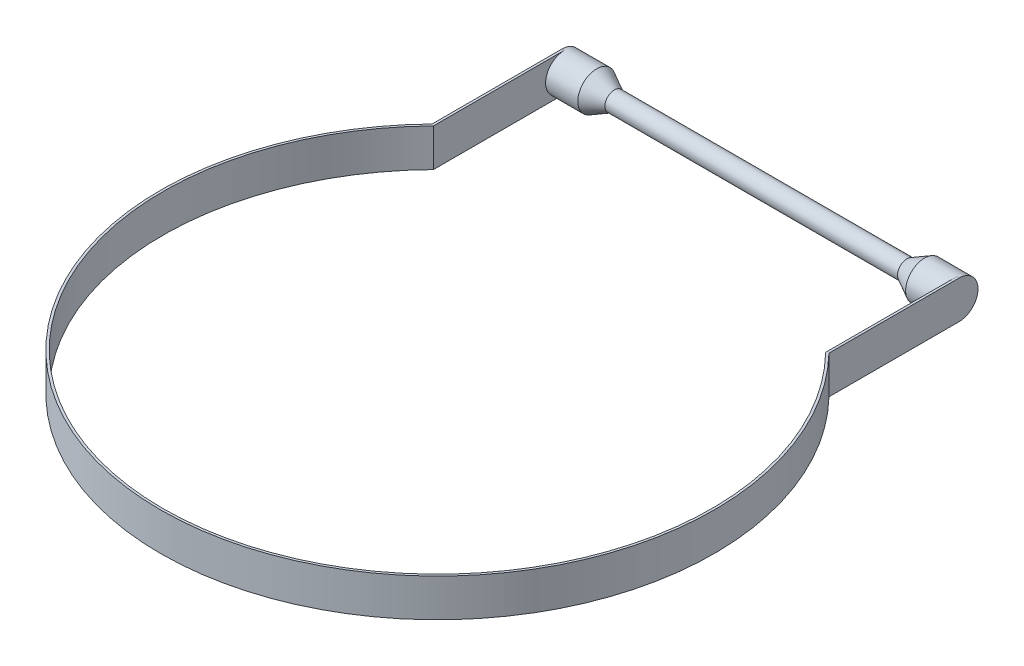
SolidWorks part; units mm, degrees
ref_plane "Plano frontal" through (0, 0, 0) normal (0, 0, 1) x (1, 0, 0)
ref_plane "Plano superior" through (0, 0, 0) normal (0, 1, 0) x (1, 0, 0)
ref_plane "Plano direito" through (0, 0, 0) normal (1, 0, 0) x (0, 0, -1)
sketch "Sketch1" plane through (0, 0, 0) normal (0, 1, 0) x (1, 0, 0)
  line L0 (-250, 0) -> (250, 0)
  line L1 (-250, 0) -> (-250, 24.125)
  line L2 (-250, 24.125) -> (-209, 24.125)
  line L3 (-186.4955, 12.0625) -> (0, 12.0625)
  line L4 (-209, 24.125) -> (-186.4955, 12.0625)
  line L9 (0, 0) -> (0, -61.9409) construction
  line L10 (250, 0) -> (250, 24.125)
  line L14 (209, 24.125) -> (186.4955, 12.0625)
  line L15 (186.4955, 12.0625) -> (0, 12.0625)
  line L16 (250, 24.125) -> (209, 24.125)
revolve "Revolve1" add sketch "Sketch1" angle 360 about L0
sketch "Sketch3" plane through (0, 0, 0) normal (0, 1, 0) x (1, 0, 0)
  line L0 (0, 12.0625) -> (0, -412.0625) construction
  line L1 (186.4955, 12.0625) -> (-186.4955, 12.0625) construction
  line L2 (-250, 0) -> (-250, -167.1135)
  line L4 (250, 0) -> (250, -167.1135)
  line L6 (-250, 24.125) -> (-250, 0)
  line L7 (250, 24.125) -> (250, 0)
  line L8 (-253.005, 24.125) -> (-253.005, 0)
  line L9 (-253.005, 0) -> (-253.005, -165.8898)
  line L10 (253.005, 0) -> (253.005, -165.8898)
  line L11 (253.005, 24.125) -> (253.005, 0)
  line L12 (-253.005, 24.125) -> (-250, 24.125)
  line L14 (253.005, 24.125) -> (250, 24.125)
  arc A0 (-250, -167.1135) -> (250, -167.1135) centre (0, -412.0625) ccw
  arc A1 (-253.005, -165.8898) -> (253.005, -165.8898) centre (0, -412.0625) ccw
  dimension "D1" = 3.005
extrude "Boss-Extrude1" add sketch "Sketch3" along normal mid plane 48.25 contours L9 A1 L10 L11 L14 L7 L4 A0 L2 L6 L12 L8
sketch "Sketch4" plane through (-253.005, 0, 0) normal (-1, 0, 0) x (0, 0, 1)
  line L0 (0, 0) -> (0, 44.2727) construction
  line L1 (0, 24.125) -> (-24.125, 24.125)
  line L2 (-24.125, 24.125) -> (-24.125, -24.125)
  line L3 (-24.125, -24.125) -> (0, -24.125)
  arc A0 (0, 24.125) -> (0, -24.125) centre (0, 0) ccw
  line M1 (-24.125, -24.125) -> (165.8898, -24.125)
  line M3 (165.8898, 24.125) -> (-24.125, 24.125)
  line M4 (-24.125, 24.125) -> (-24.125, -24.125)
extrude "Cut-Extrude1" cut sketch "Sketch4" against normal through all contours A0 M3 M4 | A0 L2 M1
